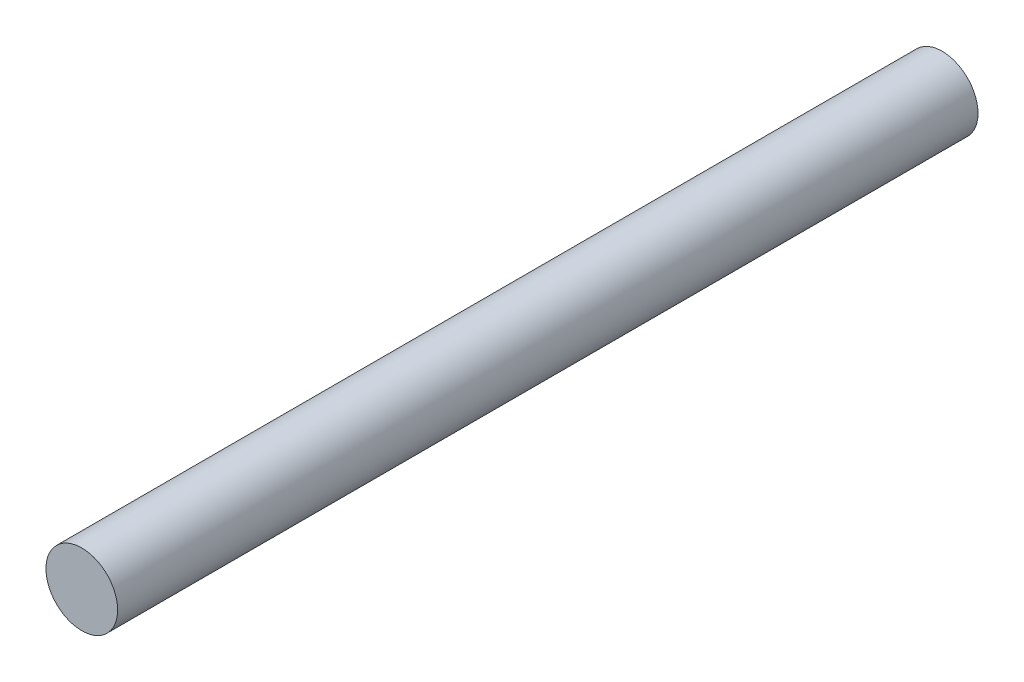
SolidWorks part; units mm, degrees
ref_plane "Front Plane" through (0, 0, 0) normal (0, 0, 1) x (1, 0, 0)
ref_plane "Top Plane" through (0, 0, 0) normal (0, 1, 0) x (1, 0, 0)
ref_plane "Right Plane" through (0, 0, 0) normal (1, 0, 0) x (0, 0, -1)
sketch "Sketch1" plane through (0, 0, 0) normal (0, 0, 1) x (1, 0, 0)
  circle A0 centre (0, 0) radius 1
  dimension "D1" = 2
extrude "Boss-Extrude1" add sketch "Sketch1" along normal blind 24
